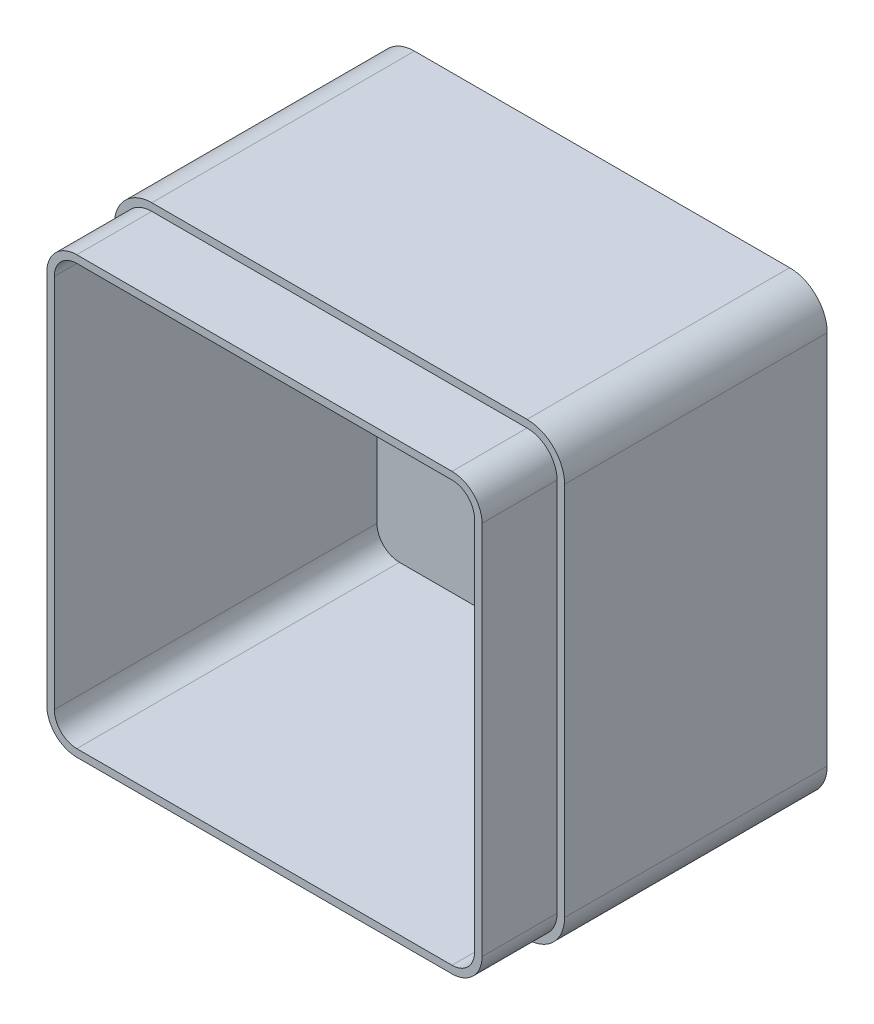
SolidWorks part; units mm, degrees
ref_plane "Front Plane" through (0, 0, 0) normal (0, 0, 1) x (1, 0, 0)
ref_plane "Top Plane" through (0, 0, 0) normal (0, 1, 0) x (1, 0, 0)
ref_plane "Right Plane" through (0, 0, 0) normal (1, 0, 0) x (0, 0, -1)
sketch "Sketch1" plane through (0, 0, 0) normal (0, 0, 1) x (1, 0, 0)
  line L1 (0, 0) -> (120, 0)
  line L2 (0, 0) -> (0, 120)
  line L3 (0, 120) -> (120, 120)
  line L4 (120, 0) -> (120, 120)
  dimension "D1" = 120
  dimension "D2" = 120
extrude "Boss-Extrude1" add sketch "Sketch1" along normal blind 90
fillet "Fillet1" radius 10 4 edges at (120, 0, 45) (0, 0, 45) (0, 120, 45) (120, 120, 45)
shell "Shell1" thickness 4
sketch "Sketch2" plane through (0, 0, 90) normal (0, 0, 1) x (1, 0, 0)
  line L4 (10, 0) -> (110, 0)
  line L5 (120, 10) -> (120, 110)
  line L6 (110, 120) -> (10, 120)
  line L7 (0, 110) -> (0, 10)
  line L8 (10, 0) -> (110, 0)
  line L9 (120, 10) -> (120, 110)
  line L10 (110, 120) -> (10, 120)
  line L11 (0, 110) -> (0, 10)
  arc A4 (110, 0) -> (120, 10) centre (110, 10) ccw
  arc A5 (120, 110) -> (110, 120) centre (110, 110) ccw
  arc A6 (10, 120) -> (0, 110) centre (10, 110) ccw
  arc A7 (0, 10) -> (10, 0) centre (10, 10) ccw
  arc A8 (110, 0) -> (120, 10) centre (110, 10) ccw
  arc A9 (120, 110) -> (110, 120) centre (110, 110) ccw
  arc A10 (10, 120) -> (0, 110) centre (10, 110) ccw
  arc A11 (0, 10) -> (10, 0) centre (10, 10) ccw
  dimension "D1" = 0
sketch "Sketch3" plane through (0, 0, 90) normal (0, 0, 1) x (1, 0, 0)
  line L0 (10, 2) -> (110, 2)
  line L1 (118, 10) -> (118, 110)
  line L2 (110, 118) -> (10, 118)
  line L3 (2, 110) -> (2, 10)
  line L4 (10, 0) -> (110, 0)
  line L5 (120, 10) -> (120, 110)
  line L6 (110, 120) -> (10, 120)
  line L7 (0, 110) -> (0, 10)
  line L8 (10, 0) -> (110, 0)
  line L9 (120, 10) -> (120, 110)
  line L10 (110, 120) -> (10, 120)
  line L11 (0, 110) -> (0, 10)
  arc A0 (110, 2) -> (118, 10) centre (110, 10) ccw
  arc A1 (118, 110) -> (110, 118) centre (110, 110) ccw
  arc A2 (10, 118) -> (2, 110) centre (10, 110) ccw
  arc A3 (2, 10) -> (10, 2) centre (10, 10) ccw
  arc A4 (110, 0) -> (120, 10) centre (110, 10) ccw
  arc A5 (120, 110) -> (110, 120) centre (110, 110) ccw
  arc A6 (10, 120) -> (0, 110) centre (10, 110) ccw
  arc A7 (0, 10) -> (10, 0) centre (10, 10) ccw
  arc A8 (110, 0) -> (120, 10) centre (110, 10) ccw
  arc A9 (120, 110) -> (110, 120) centre (110, 110) ccw
  arc A10 (10, 120) -> (0, 110) centre (10, 110) ccw
  arc A11 (0, 10) -> (10, 0) centre (10, 10) ccw
  dimension "D1" = 0
  dimension "D2" = 2
extrude "Cut-Extrude1" cut sketch "Sketch3" against normal blind 20
